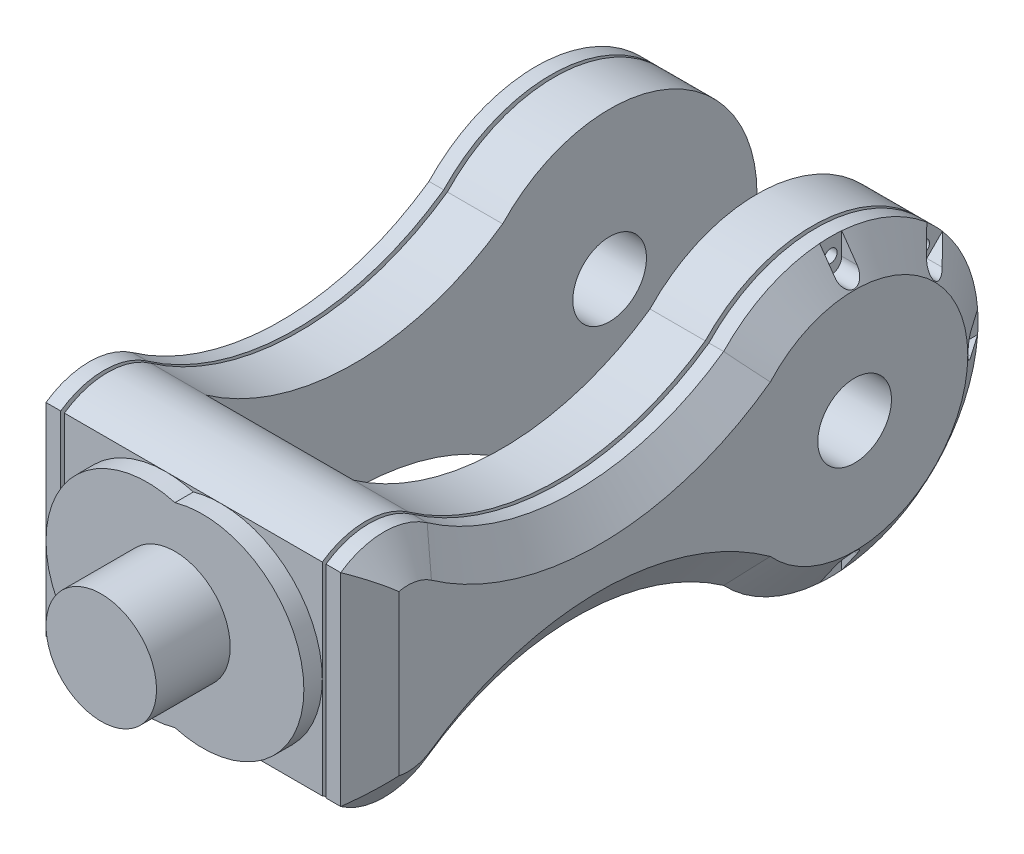
SolidWorks part; units mm, degrees
ref_plane "Front Plane" through (0, 0, 0) normal (0, 0, 1) x (1, 0, 0)
ref_plane "Top Plane" through (0, 0, 0) normal (0, 1, 0) x (1, 0, 0)
ref_plane "Right Plane" through (0, 0, 0) normal (1, 0, 0) x (0, 0, -1)
sketch "Sketch1" plane through (0, 0, 0) normal (0, 0, 1) x (1, 0, 0)
  circle A0 centre (0, 0) radius 27.5
  dimension "D1" = 55
extrude "Boss-Extrude1" add sketch "Sketch1" along normal blind 5
ref_plane "Plane1" through (27.5, 0, 0) normal (1, 0, 0) x (0, 0, -1)
sketch "Sketch2" plane through (27.5, 0, 0) normal (1, 0, 0) x (0, 0, -1)
  line L0 (0, 27.5) -> (0, -27.5)
  arc A0 (0, 27.5) -> (23.463, 27.5) centre (11.7315, 10.8043) cw
  arc A1 (23.463, 27.5) -> (103.9526, 27.5) centre (63.7078, 84.7744) ccw
  arc A2 (23.463, -27.5) -> (103.9526, -27.5) centre (63.7078, -84.7744) cw
  arc A3 (0, -27.5) -> (23.463, -27.5) centre (11.7315, -10.8043) ccw
  arc A4 (103.9526, -27.5) -> (103.9526, 27.5) centre (133, 0) ccw
  dimension "D2" = 70
  dimension "D3" = 80
extrude "Boss-Extrude2" add sketch "Sketch2" along normal blind 15 separate body
sketch "Sketch3" plane through (42.5, 0, 0) normal (1, 0, 0) x (0, 0, -1)
  line L2 (2.5, 26.1463) -> (2.5, -26.1463)
  line L3 (2.5, 26.1463) -> (2.5, -26.1463)
  arc A10 (22.0257, 25.4545) -> (2.5, 26.1463) centre (11.7315, 10.8043) ccw
  arc A11 (2.5, -26.1463) -> (22.0257, -25.4545) centre (11.7315, -10.8043) ccw
  arc A12 (105.6003, -25.6029) -> (22.0257, -25.4545) centre (63.7078, -84.7744) ccw
  arc A13 (105.6003, -25.6029) -> (105.6003, 25.6029) centre (133, 0) ccw
  arc A14 (22.0257, 25.4545) -> (105.6003, 25.6029) centre (63.7078, 84.7744) ccw
  arc A15 (22.0257, 25.4545) -> (2.5, 26.1463) centre (11.7315, 10.8043) ccw
  arc A16 (2.5, -26.1463) -> (22.0257, -25.4545) centre (11.7315, -10.8043) ccw
  arc A17 (105.6003, -25.6029) -> (22.0257, -25.4545) centre (63.7078, -84.7744) ccw
  arc A18 (105.6003, -25.6029) -> (105.6003, 25.6029) centre (133, 0) ccw
  arc A19 (22.0257, 25.4545) -> (105.6003, 25.6029) centre (63.7078, 84.7744) ccw
  dimension "D1" = 2.5
extrude "Boss-Extrude3" add sketch "Sketch3" along normal blind 1
sketch "Sketch4" plane through (43.5, 0, 0) normal (1, 0, 0) x (0, 0, -1)
  line L3 (0, 27.5) -> (0, -27.5)
  line L4 (0, 27.5) -> (0, -27.5)
  arc A15 (23.463, 27.5) -> (0, 27.5) centre (11.7315, 10.8043) ccw
  arc A16 (0, -27.5) -> (23.463, -27.5) centre (11.7315, -10.8043) ccw
  arc A17 (103.9526, -27.5) -> (23.463, -27.5) centre (63.7078, -84.7744) ccw
  arc A18 (103.9526, -27.5) -> (103.9526, 27.5) centre (133, 0) ccw
  arc A19 (23.463, 27.5) -> (103.9526, 27.5) centre (63.7078, 84.7744) ccw
  arc A20 (23.463, 27.5) -> (0, 27.5) centre (11.7315, 10.8043) ccw
  arc A21 (0, -27.5) -> (23.463, -27.5) centre (11.7315, -10.8043) ccw
  arc A22 (103.9526, -27.5) -> (23.463, -27.5) centre (63.7078, -84.7744) ccw
  arc A23 (103.9526, -27.5) -> (103.9526, 27.5) centre (133, 0) ccw
  arc A24 (23.463, 27.5) -> (103.9526, 27.5) centre (63.7078, 84.7744) ccw
  dimension "D2" = 0
extrude "Boss-Extrude4" add sketch "Sketch4" along normal blind 4
sketch "Sketch6" plane through (47.5, 0, 0) normal (1, 0, 0) x (0, 0, -1)
  line L1 (0, 27.5) -> (0, -27.5)
  line L2 (0, 27.5) -> (0, -27.5)
  arc A5 (23.463, 27.5) -> (103.9526, 27.5) centre (63.7078, 84.7744) ccw
  arc A6 (23.463, 27.5) -> (0, 27.5) centre (11.7315, 10.8043) ccw
  arc A7 (0, -27.5) -> (23.463, -27.5) centre (11.7315, -10.8043) ccw
  arc A8 (103.9526, -27.5) -> (23.463, -27.5) centre (63.7078, -84.7744) ccw
  arc A9 (103.9526, -27.5) -> (103.9526, 27.5) centre (133, 0) ccw
  arc A10 (23.463, 27.5) -> (103.9526, 27.5) centre (63.7078, 84.7744) ccw
  arc A11 (23.463, 27.5) -> (0, 27.5) centre (11.7315, 10.8043) ccw
  arc A12 (0, -27.5) -> (23.463, -27.5) centre (11.7315, -10.8043) ccw
  arc A13 (103.9526, -27.5) -> (23.463, -27.5) centre (63.7078, -84.7744) ccw
  arc A14 (103.9526, -27.5) -> (103.9526, 27.5) centre (133, 0) ccw
  dimension "D1" = 0
extrude "Boss-Extrude5" add sketch "Sketch6" along normal blind 6.5 draft 55
sketch "Sketch7" plane through (54, 0, 0) normal (1, 0, 0) x (0, 0, -1)
  line L0 (0, 0) -> (194.4852, 0) construction
  line L1 (166.8873, 3) -> (172.8873, 3)
  line L2 (166.8873, -3) -> (172.8873, -3)
  arc A0 (103.9526, -27.5) -> (103.9526, 27.5) centre (133, 0) ccw construction
  arc A1 (166.8873, 3) -> (166.8873, -3) centre (166.8873, 0) ccw
  arc A2 (172.8873, 3) -> (172.8873, -3) centre (168.8873, 0) cw
  dimension "D3" = 5
  dimension "D4" = 3
  dimension "D1" = 6
  dimension "D2" = 3
extrude "Cut-Extrude1" cut sketch "Sketch7" against normal blind 6.5
sketch "Sketch8" plane through (47.5, 0, 0) normal (1, 0, 0) x (0, 0, -1)
  line L0 (163.8873, 0) -> (173, 0) construction
  arc A0 (166.8873, 3) -> (166.8873, -3) centre (166.8873, 0) ccw construction
  arc A1 (172.8873, -3) -> (172.8873, 3) centre (133, 0) ccw construction
  circle A2 centre (168.4437, 0) radius 1.75
  dimension "D1" = 3.5
extrude "Cut-Extrude2" cut sketch "Sketch8" against normal blind 5
pattern_circular "CirPattern2" count 3 every 45 about axis through (0, 0, -133) along (1, 0, 0) of "Cut-Extrude1", "Cut-Extrude2"
sketch "Sketch9" plane through (27.5, 0, 0) normal (-1, 0, 0) x (0, 0, 1)
  line L0 (-23.463, 27.5) -> (-23.463, -27.5)
  line L1 (0, -27.5) -> (0, 27.5)
  line L2 (0, -27.5) -> (0, 27.5)
  arc A5 (0, 27.5) -> (-23.463, 27.5) centre (-11.7315, 10.8043) ccw
  arc A6 (-103.9526, 27.5) -> (-23.463, 27.5) centre (-63.7078, 84.7744) ccw
  arc A7 (-103.9526, 27.5) -> (-103.9526, -27.5) centre (-133, 0) ccw
  arc A8 (-23.463, -27.5) -> (-103.9526, -27.5) centre (-63.7078, -84.7744) ccw
  arc A9 (-23.463, -27.5) -> (0, -27.5) centre (-11.7315, -10.8043) ccw
  arc A10 (0, 27.5) -> (-23.463, 27.5) centre (-11.7315, 10.8043) ccw
  arc A14 (-23.463, -27.5) -> (0, -27.5) centre (-11.7315, -10.8043) ccw
  dimension "D1" = 0
extrude "Boss-Extrude6" add sketch "Sketch9" along normal blind 40
ref_plane "Plane2" through (7.5, 0, 0) normal (-1, 0, 0) x (0, 0, 1)
mirror "Mirror3" about plane through (7.5, 0, 0) normal (-1, 0, 0) of bodies 109
sketch "Sketch10" plane through (0, 0, 5) normal (0, 0, 1) x (1, 0, 0)
  line L0 (7.5, 26.4575) -> (7.5, -26.4575) construction
  circle A0 centre (7.5, 0) radius 15
  dimension "D1" = 30
extrude "Boss-Extrude7" add sketch "Sketch10" along normal blind 20
sketch "Sketch11" plane through (-39, 0, 0) normal (-1, 0, 0) x (0, 0, 1)
  circle A0 centre (-133, 0) radius 10
  dimension "D1" = 20
extrude "Cut-Extrude3" cut sketch "Sketch11" against normal through all
